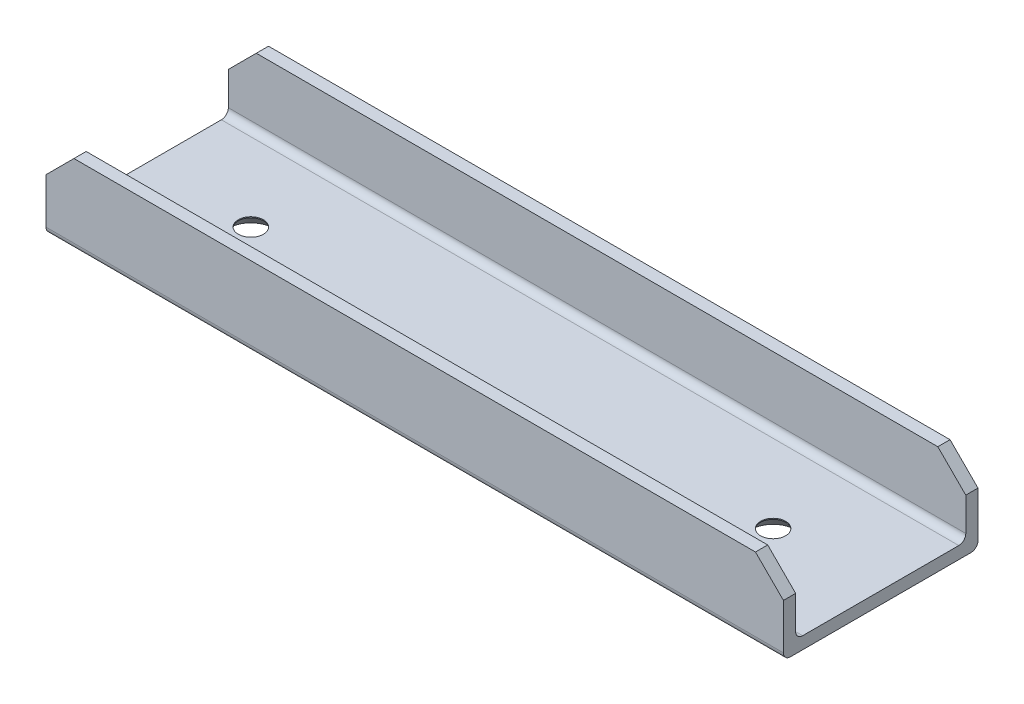
SolidWorks part; units mm, degrees
ref_plane "Front Plane" through (0, 0, 0) normal (0, 0, 1) x (1, 0, 0)
ref_plane "Top Plane" through (0, 0, 0) normal (0, 1, 0) x (1, 0, 0)
ref_plane "Right Plane" through (0, 0, 0) normal (1, 0, 0) x (0, 0, -1)
sketch "Sketch1" plane through (0, 0, 0) normal (0, 1, 0) x (1, 0, 0)
  line L1 (-52.775, -13.925) -> (52.775, -13.925)
  line L2 (-52.775, -13.925) -> (-52.775, 13.925)
  line L3 (-52.775, 13.925) -> (52.775, 13.925)
  line L4 (52.775, -13.925) -> (52.775, 13.925)
  line L5 (-52.775, -13.925) -> (52.775, 13.925) construction
  line L6 (-52.775, 13.925) -> (52.775, -13.925) construction
  point P0 (0, 0)
  dimension "D1" = 27.85
  dimension "D2" = 105.55
extrude "Boss-Extrude1" add sketch "Sketch1" along normal blind 11.5
sketch "Sketch2" plane through (0, 11.5, 0) normal (0, 1, 0) x (1, 0, 0)
  line L0 (52.775, -13.925) -> (52.775, 13.925) construction
  line L1 (-52.775, -12.175) -> (52.775, -12.175)
  line L2 (-52.775, -12.175) -> (-52.775, 12.175)
  line L3 (-52.775, 12.175) -> (52.775, 12.175)
  line L4 (52.775, -12.175) -> (52.775, 12.175)
  line L5 (-52.775, -12.175) -> (52.775, 12.175) construction
  line L6 (-52.775, 12.175) -> (52.775, -12.175) construction
  line L7 (52.775, 13.925) -> (-52.775, 13.925) construction
  point P0 (0, 0)
  dimension "D1" = 1.75
extrude "Cut-Extrude1" cut sketch "Sketch2" against normal offset from surface (9.75 mm away) 1.75 up to face at (0, 0, 0)
chamfer "Chamfer1" distance 4 angle 45 4 edges at (-52.775, 11.5, -13.05) (-52.775, 11.5, 13.05) (52.775, 11.5, -13.05) (52.775, 11.5, 13.05)
fillet "Fillet1" radius 1 4 edges at (0, 1.75, -12.175) (0, 1.75, 12.175) (0, 0, -13.925) (0, 0, 13.925)
hole_wizard "Hole1" positions "3DSketch1" profile "Sketch3" legacy end condition through all
sketch3d "3DSketch1"
  line L0 (-52.775, 0, -12.925) -> (-52.775, 0, 12.925) construction
  line L1 (52.775, 0, 12.925) -> (52.775, 0, -12.925) construction
  point P0 (-37.375, 0, 0)
  point P2 (37.375, 0, 0)
  point P10 (0, 0, 0)
  point P11 (-52.775, 0, 0)
  point P12 (0, 0, 0)
  point P13 (0, 0, 0)
  dimension "D1" = 15.4
  dimension "D2" = 15.4
sketch "Sketch3" plane through (-37.375, 0, 0) normal (1, 0, 0) x (0, 0, -1)
  line L0 (0, 0) -> (0, 11.5)
  line L1 (0, 11.5) -> (1.8, 11.5)
  line L2 (1.8, 11.5) -> (1.8, 1.6105)
  line L3 (1.8, 1.6105) -> (3.2, 0)
  line L4 (3.2, 0) -> (0, 0)
  line L5 (0, -6.4453) -> (0, 115.525) construction
  line L6 (-1.8, 1.6105) -> (-3.2, 0) construction
  dimension "Diameter" = 3.6
  dimension "Depth" = 11.5
  dimension "C-Sink Angle" = 82
  dimension "C-Sink Diameter" = 6.4
